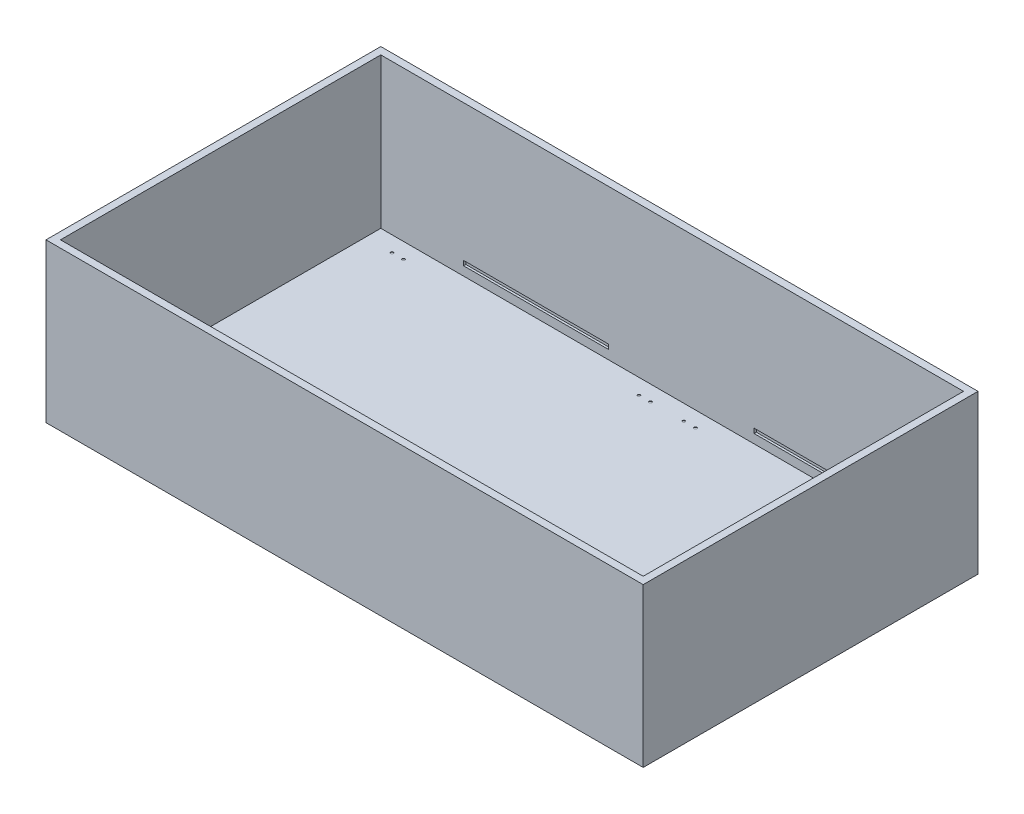
SolidWorks part; units mm, degrees
ref_plane "Alzado" through (0, 0, 0) normal (0, 0, 1) x (1, 0, 0)
ref_plane "Planta" through (0, 0, 0) normal (0, 1, 0) x (1, 0, 0)
ref_plane "Vista lateral" through (0, 0, 0) normal (1, 0, 0) x (0, 0, -1)
sketch "Croquis1" plane through (0, 0, 0) normal (0, 1, 0) x (1, 0, 0)
  line L1 (-660, -370) -> (660, -370)
  line L2 (-660, -370) -> (-660, 370)
  line L3 (-660, 370) -> (660, 370)
  line L4 (660, -370) -> (660, 370)
  line L5 (-660, -370) -> (660, 370) construction
  line L6 (-660, 370) -> (660, -370) construction
  point P0 (0, 0)
  dimension "D1" = 740
  dimension "D2" = 1320
extrude "Saliente-Extruir1" add sketch "Croquis1" along normal blind 350
sketch "Croquis2" plane through (0, 350, 0) normal (0, 1, 0) x (1, 0, 0)
  line L1 (-644, -354) -> (644, -354)
  line L2 (-644, -354) -> (-644, 354)
  line L3 (-644, 354) -> (644, 354)
  line L4 (644, -354) -> (644, 354)
  line L5 (-644, -354) -> (644, 354) construction
  line L6 (-644, 354) -> (644, -354) construction
  line L7 (-660, 370) -> (-660, -370) construction
  line L8 (660, 370) -> (-660, 370) construction
  point P0 (0, 0)
  dimension "D1" = 16
  dimension "D2" = 16
extrude "Cortar-Extruir1" cut sketch "Croquis2" against normal blind 332
hole_wizard "Taladro de margen para M61" positions "Croquis3" profile "Croquis4" hole size "M6" standard "Ansi Metric"
sketch "Croquis3" plane through (275.0401, 18, -214.4233) normal (0, 1, 0) x (1, 0, 0)
  point P0 (-831.1645, -520.3523)
  point P3 (-831.1645, -546.0552)
  point P6 (-855.6646, -546.0552)
  point P9 (-855.6646, -520.3523)
sketch "Croquis4" plane through (-556.1244, 18, 305.929) normal (1, 0, 0) x (0, 0, 1)
  line L0 (0, 0) -> (0, 1)
  line L1 (0, 1) -> (3, 1)
  line L2 (3, 1) -> (3, 0)
  line L3 (3, 0) -> (0, 0)
  line L4 (0, 1) -> (-3, 1) construction
  line L5 (0, -6.35) -> (0, 107.95) construction
  dimension "Diámetro de taladro" = 6
  dimension "Profundidad de taladro" = 1
  dimension "Ángulo de perforador" = 180
hole_wizard "Taladro de margen para M62" positions "Croquis5" profile "Croquis6" hole size "M6" standard "Ansi Metric"
sketch "Croquis5" plane through (275.0401, 18, -214.4233) normal (0, 1, 0) x (1, 0, 0)
  point P0 (-859.8001, 105.0767)
  point P2 (-834.3005, 105.0756)
  point P4 (-314.0397, 105.0756)
  point P6 (-288.5401, 105.0756)
  point P8 (-214.748, 105.0756)
  point P15 (-188.9697, 105.0756)
  point P17 (326.9147, 105.0756)
  point P19 (352.4143, 105.0756)
  point P21 (323.9211, -520.3523)
  point P24 (348.4211, -520.3523)
  point P27 (348.4211, -546.0552)
  point P30 (323.9211, -546.0552)
  point P33 (-185.7932, -520.3523)
  point P36 (-185.7932, -546.0552)
  point P39 (-214.6491, -547.2971)
  point P43 (-210.2932, -520.3523)
  point P46 (-292.458, -520.3523)
  point P49 (-292.458, -546.0552)
  point P52 (-316.958, -546.0552)
  point P55 (-316.958, -520.3523)
sketch "Croquis6" plane through (-584.76, 18, -319.5) normal (1, 0, 0) x (0, 0, 1)
  line L0 (0, 0) -> (0, 1)
  line L1 (0, 1) -> (3, 1)
  line L2 (3, 1) -> (3, 0)
  line L3 (3, 0) -> (0, 0)
  line L4 (0, 1) -> (-3, 1) construction
  line L5 (0, -6.35) -> (0, 107.95) construction
  dimension "Diámetro de taladro" = 6
  dimension "Profundidad de taladro" = 1
  dimension "Ángulo de perforador" = 180
extrude "Cortar-Extruir2" cut sketch "Croquis7" against normal blind 320 from offset 143 offset against normal yes
sketch "Croquis7" plane through (644, 0, -214.4233) normal (1, 0, 0) x (0, 0, -1)
  line L1 (139.5767, 37.7862) -> (144.5767, 37.7862)
  line L2 (139.5767, 37.7862) -> (139.5767, 48.1145)
  line L3 (139.5767, 48.1145) -> (144.5767, 48.1145)
  line L4 (144.5767, 37.7862) -> (144.5767, 48.1145)
extrude "Cortar-Extruir3" cut sketch "Croquis8" against normal blind 320 from offset 183
sketch "Croquis8" plane through (-644, 0, -214.4233) normal (-1, 0, 0) x (0, 0, 1)
  line L1 (-139.5767, 48.1145) -> (-144.5767, 48.1145)
  line L2 (-139.5767, 48.1145) -> (-139.5767, 37.7862)
  line L3 (-139.5767, 37.7862) -> (-144.5767, 37.7862)
  line L4 (-144.5767, 48.1145) -> (-144.5767, 37.7862)
